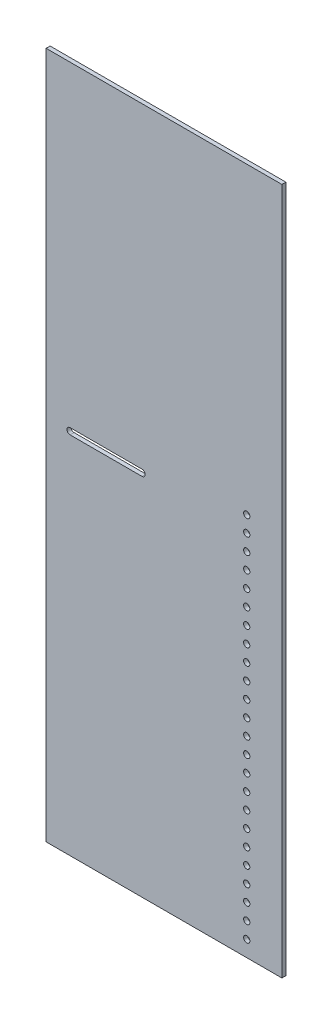
SolidWorks part; units mm, degrees
ref_plane "Front Plane" through (0, 0, 0) normal (1, 0, 0) x (0, 1, 0)
ref_plane "Top Plane" through (0, 0, 0) normal (0, 0, 1) x (0, 1, 0)
ref_plane "Right Plane" through (0, 0, 0) normal (0, 1, 0) x (-1, 0, 0)
sketch "Sketch1" plane through (0, 0, 0) normal (0, 0, 1) x (0, 1, 0)
  line L1 (-273.05, -93.6625) -> (273.05, -93.6625)
  line L2 (-273.05, -93.6625) -> (-273.05, 93.6625)
  line L3 (-273.05, 93.6625) -> (273.05, 93.6625)
  line L4 (273.05, -93.6625) -> (273.05, 93.6625)
  line L5 (-273.05, -93.6625) -> (273.05, 93.6625) construction
  line L6 (-273.05, 93.6625) -> (273.05, -93.6625) construction
  point P0 (0, 0)
  dimension "D1" = 546.1
  dimension "D2" = 187.325
extrude "Boss-Extrude1" add sketch "Sketch1" along normal blind 3.175
sketch "Sketch2" plane through (0, 0, 3.175) normal (0, 0, 1) x (1, 0, 0)
  line L0 (-93.6625, 273.05) -> (-93.6625, -273.05) construction
  line L1 (-93.6625, -273.05) -> (93.6625, -273.05) construction
  line L2 (-74.6125, 16.5608) -> (-17.4625, 16.5608)
  line L3 (-17.4625, 21.5392) -> (-74.6125, 21.5392)
  circle A0 centre (-74.6125, 19.05) radius 2.4892 construction
  circle A1 centre (-17.4625, 19.05) radius 2.4892 construction
  arc A2 (-74.6125, 16.5608) -> (-74.6125, 21.5392) centre (-74.6125, 19.05) cw
  arc A3 (-17.4625, 16.5608) -> (-17.4625, 21.5392) centre (-17.4625, 19.05) ccw
  point P0 (-17.4625, 19.05)
  point P1 (-74.6125, 19.05)
  dimension "D4" = 4.9784
  dimension "D1" = 57.15
  dimension "D2" = 19.05
  dimension "D3" = 292.1
extrude "Cut-Extrude1" cut sketch "Sketch2" against normal through all
sketch "Sketch3" plane through (0, 0, 3.175) normal (0, 0, 1) x (1, 0, 0)
  line L0 (93.6625, -273.05) -> (93.6625, 273.05) construction
  line L1 (-93.6625, -273.05) -> (93.6625, -273.05) construction
  point P0 (65.7225, -260.35)
  point P3 (65.7225, -247.65)
  point P4 (65.7225, -234.95)
  point P5 (65.7225, -222.25)
  point P6 (65.7225, -209.55)
  point P7 (65.7225, -196.85)
  point P8 (65.7225, -184.15)
  point P9 (65.7225, -171.45)
  point P10 (65.7225, -158.75)
  point P11 (65.7225, -146.05)
  point P12 (65.7225, -133.35)
  point P13 (65.7225, -120.65)
  point P14 (65.7225, -107.95)
  point P15 (65.7225, -95.25)
  point P16 (65.7225, -82.55)
  point P17 (65.7225, -69.85)
  point P18 (65.7225, -57.15)
  point P19 (65.7225, -44.45)
  point P20 (65.7225, -31.75)
  point P21 (65.7225, -19.05)
  point P22 (65.7225, -6.35)
  point P23 (65.7225, 6.35)
  point P24 (65.7225, 19.05)
  point P25 (65.7225, 31.75)
  dimension "D2" = 27.94
  dimension "D3" = 12.7
  dimension "D4" = 12.7
  dimension "D1" = 24
hole_wizard "#9 (0.196) Diameter Hole1" positions "Sketch3" profile "Sketch4" hole size "#9" standard "ANSI Inch" end condition through all
sketch "Sketch4" plane through (65.7225, -260.35, 3.175) normal (1, 0, 0) x (0, -1, 0)
  line L0 (0, 0) -> (0, 3.175)
  line L1 (0, 3.175) -> (2.4892, 3.175)
  line L2 (2.4892, 3.175) -> (2.4892, 0)
  line L5 (2.4892, 0) -> (0, 0)
  line L11 (0, -6.35) -> (0, 107.95) construction
  dimension "Thru Hole Dia." = 4.9784
  dimension "Thru Hole Depth" = 3.175
